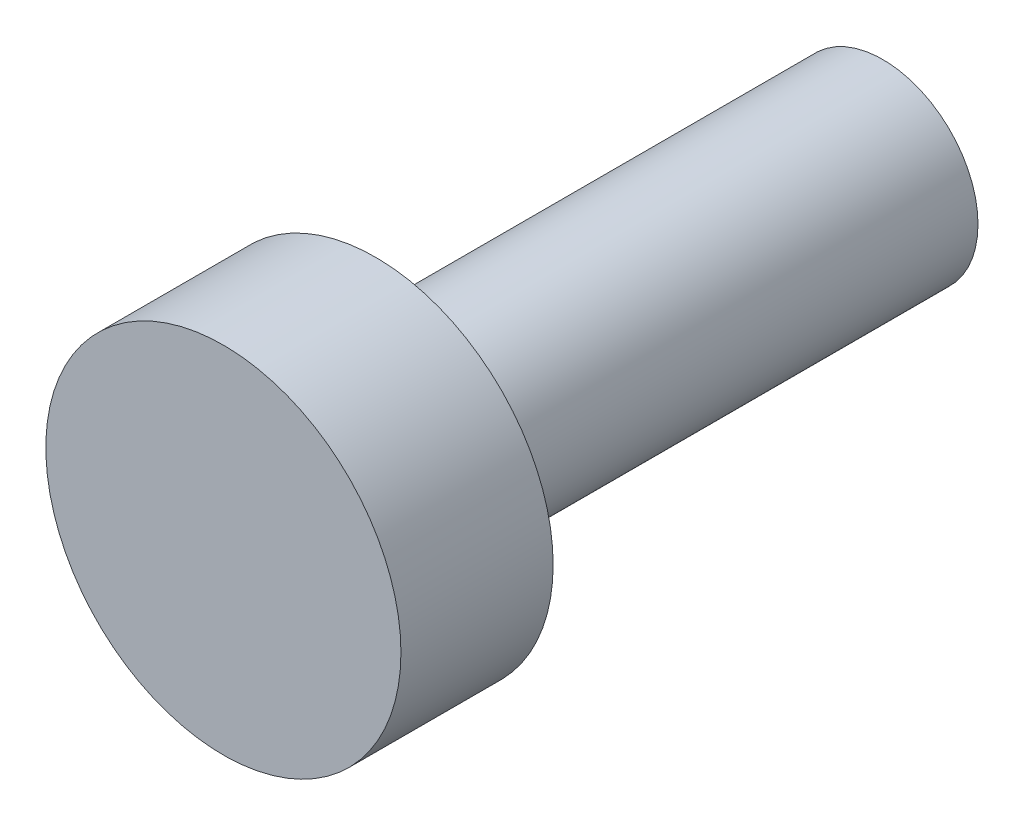
SolidWorks part; units mm, degrees
ref_plane "Plan de face" through (0, 0, 0) normal (0, 0, 1) x (1, 0, 0)
ref_plane "Plan de dessus" through (0, 0, 0) normal (0, 1, 0) x (1, 0, 0)
ref_plane "Plan de droite" through (0, 0, 0) normal (1, 0, 0) x (0, 0, -1)
sketch "Esquisse1" plane through (0, 0, 0) normal (0, 0, 1) x (1, 0, 0)
  circle A0 centre (0, 0) radius 2.8
  dimension "D1" = 5.6
extrude "Boss.-Extru.1" add sketch "Esquisse1" along normal blind 2.4
sketch "Esquisse2" plane through (0, 0, 0) normal (0, 0, -1) x (-1, 0, 0)
  circle A0 centre (0, 0) radius 1.5
  dimension "D1" = 3
extrude "Boss.-Extru.2" add sketch "Esquisse2" along normal blind 8
